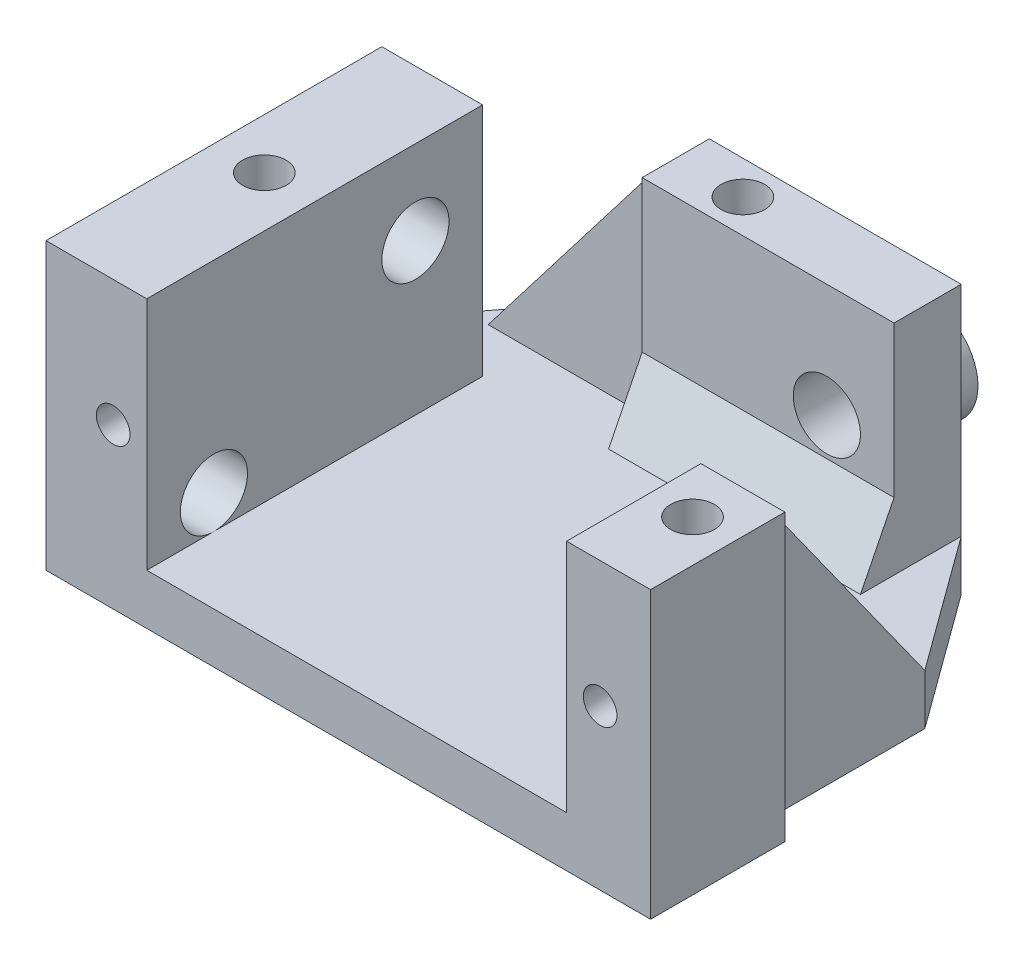
SolidWorks part; units mm, degrees
ref_plane "Front Plane" through (0, 0, 0) normal (0, 0, 1) x (1, 0, 0)
ref_plane "Top Plane" through (0, 0, 0) normal (0, 1, 0) x (1, 0, 0)
ref_plane "Right Plane" through (0, 0, 0) normal (1, 0, 0) x (0, 0, -1)
sketch "Sketch1" plane through (0, 0, 0) normal (0, 1, 0) x (1, 0, 0)
  line L1 (-25, 18) -> (25, 18)
  line L2 (-25, 18) -> (-25, -18)
  line L3 (-25, -18) -> (25, -18)
  line L4 (25, 18) -> (25, -18)
  point P4 (0, 18)
  point P6 (-25, 0)
  dimension "D1" = 50
  dimension "D2" = 36
extrude "Boss-Extrude1" add sketch "Sketch1" along normal blind 3
sketch "Sketch2" plane through (0, 3, 0) normal (0, 1, 0) x (1, 0, 0)
  line L0 (-25, -18) -> (25, -18) construction
  line L1 (25, -8) -> (20, -8)
  line L2 (25, -8) -> (25, 0)
  line L3 (25, 0) -> (20, 0)
  line L4 (20, -8) -> (20, 0)
  line L5 (-5, -8) -> (-11, -8)
  line L6 (-5, -8) -> (-5, 12)
  line L7 (-5, 12) -> (-11, 12)
  line L8 (-11, -8) -> (-11, 12)
  line L9 (25, -18) -> (25, 18) construction
  dimension "D1" = 25
  dimension "D2" = 8
  dimension "D3" = 10
  dimension "D4" = 5
  dimension "D5" = 0
  dimension "D6" = 20
  dimension "D7" = 6
extrude "Boss-Extrude2" add sketch "Sketch2" along normal blind 14
sketch "Sketch3" plane through (0, 3, 0) normal (0, 1, 0) x (1, 0, 0)
  line L0 (20, -8) -> (25, -8) construction
  line L1 (2.5, 14) -> (17.5, 14)
  line L2 (2.5, 14) -> (2.5, 18)
  line L3 (2.5, 18) -> (17.5, 18)
  line L4 (17.5, 14) -> (17.5, 18)
  line L5 (25, 0) -> (25, 18) construction
  dimension "D1" = 22
  dimension "D2" = 4
  dimension "D3" = 15
  dimension "D4" = 7.5
extrude "Boss-Extrude3" add sketch "Sketch3" along normal blind 13
sketch "Sketch4" plane through (0, 0, -18) normal (0, 0, -1) x (-1, 0, 0)
  line L0 (-25, 3) -> (-25, 0) construction
  line L2 (-25, 3) -> (-17.5, 3) construction
  circle A0 centre (-13.5, 9.25) radius 3
  point P4 (-13.5, 10.912)
  dimension "D1" = 11.5
  dimension "D2" = 6.25
  dimension "D3" = 6
extrude "Boss-Extrude4" add sketch "Sketch4" along normal blind 2 contours A0
sketch "Sketch5" plane through (0, 0, -20) normal (0, 0, -1) x (-1, 0, 0)
  circle A0 centre (-13.5, 9.25) radius 2
  dimension "D1" = 4
extrude "Cut-Extrude1" cut sketch "Sketch5" against normal blind 12
sketch "Sketch6" plane through (0, 3, 0) normal (0, 1, 0) x (1, 0, 0)
  line L0 (-11, 12) -> (-11, 18)
  line L1 (2.5, 18) -> (-25, 18) construction
  line L2 (-11, 18) -> (-25, 18)
  line L3 (-25, 18) -> (-25, -18)
  line L4 (-25, -18) -> (25, -18)
  line L5 (25, -18) -> (25, -8)
  line L6 (25, -8) -> (-11, -8)
  line L7 (-11, -8) -> (-11, 12)
extrude "Cut-Extrude2" cut sketch "Sketch6" against normal blind 11
sketch "Sketch7" plane through (0, 17, 0) normal (0, 1, 0) x (1, 0, 0)
  line L0 (25, 0) -> (20, 0) construction
  line L1 (23.3333, 0) -> (21.6667, 0)
  line L2 (23.3333, 0) -> (23.3333, 10)
  line L3 (23.3333, 10) -> (21.6667, 10)
  line L4 (21.6667, 0) -> (21.6667, 10)
  line L5 (25, 0) -> (25, 18) construction
  dimension "D1" = 1.6667
  dimension "D2" = 1.6667
  dimension "D3" = 10
extrude "Boss-Extrude5" add sketch "Sketch7" against normal up to surface (14 mm away) up to face at (8.1667, 3, -9)
sketch "Sketch8" plane through (23.3333, 0, 0) normal (1, 0, 0) x (0, 0, -1)
  line L0 (10, 3) -> (0, 17)
  line L1 (0, 17) -> (10, 17)
  line L2 (10, 17) -> (10, 3)
extrude "Cut-Extrude3" cut sketch "Sketch8" against normal up to next
sketch "Sketch9" plane through (0, 3, 0) normal (0, 1, 0) x (1, 0, 0)
  line L0 (25, 0) -> (23.3333, 0)
  line L1 (23.3333, 0) -> (23.3333, 10)
  line L2 (23.3333, 10) -> (17.5, 18)
  line L3 (17.5, 18) -> (25, 18)
  line L4 (25, 18) -> (25, 0)
extrude "Cut-Extrude4" cut sketch "Sketch9" against normal up to next contours L2 L3 L4 L0 L1
sketch "Sketch10" plane through (0, 3, 0) normal (0, 1, 0) x (1, 0, 0)
  line L0 (2.5, 18) -> (2.5, 14) construction
  line L1 (2.5, 14.8333) -> (-7.5, 14.8333)
  line L2 (2.5, 14.8333) -> (2.5, 16.5)
  line L3 (2.5, 16.5) -> (-7.5, 16.5)
  line L4 (-7.5, 14.8333) -> (-7.5, 16.5)
  line L5 (21.6667, 10) -> (23.3333, 10) construction
  line L6 (2.5, 18) -> (-11, 18) construction
  dimension "D1" = 10
  dimension "D2" = 1.5
extrude "Boss-Extrude7" add sketch "Sketch10" along normal up to surface (13 mm away) up to face at (10, 16, -16)
sketch "Sketch11" plane through (0, 0, -16.5) normal (0, 0, -1) x (-1, 0, 0)
  line L0 (7.5, 3) -> (-2.5, 16)
  line L1 (-2.5, 16) -> (7.5, 16)
  line L2 (7.5, 16) -> (7.5, 3)
extrude "Cut-Extrude5" cut sketch "Sketch11" against normal blind 2
sketch "Sketch12" plane through (-11, 0, 0) normal (-1, 0, 0) x (0, 0, 1)
  line L0 (-12, 17) -> (8, 17) construction
  line L1 (8, 17) -> (8, 0) construction
  line L2 (-12, 17) -> (-12, 3) construction
  circle A0 centre (4, 5) radius 2
  circle A1 centre (-8, 12) radius 2
  point P4 (0, 0)
  dimension "D1" = 4
  dimension "D2" = 12
  dimension "D3" = 4
  dimension "D4" = 4
  dimension "D5" = 5
extrude "Cut-Extrude6" cut sketch "Sketch12" against normal blind 6
chamfer "Chamfer1" distance 2 distance2 4 1 edges at (10, 3, -14)
sketch "Sketch13" plane through (0, 3, 0) normal (0, 1, 0) x (1, 0, 0)
  line L0 (-7.5, 16.5) -> (-11, 12)
  line L1 (-11, 12) -> (-11, 18)
  line L2 (-11, 18) -> (2.5, 18)
  line L3 (2.5, 18) -> (2.5, 16.5)
  line L4 (-7.5, 16.5) -> (2.5, 16.5)
extrude "Cut-Extrude7" cut sketch "Sketch13" against normal blind 5
sketch "Sketch14" plane through (0, 17, 0) normal (0, 1, 0) x (1, 0, 0)
  line L0 (-5, 12) -> (-11, 12) construction
  line L2 (21.6667, 0) -> (23.3333, 0) construction
  line L3 (25, 0) -> (23.3333, 0) construction
  line L4 (17.5, 14) -> (17.5, 18) construction
  line L5 (2.5, 18) -> (2.5, 16.5) construction
  line L6 (-11, 12) -> (-11, -8) construction
  circle A0 centre (6.5, 16) radius 1.3
  circle A1 centre (-8, 2) radius 1.3
  circle A2 centre (22.5, -3) radius 1.3
  point P6 (0, 0)
  point P9 (-8, 12)
  point P10 (0, 0)
  point P14 (0, 0)
  point P17 (22.5, 0)
  point P21 (0, 0)
  point P24 (17.5, 16)
  point P27 (0, 0)
  point P30 (-11, 2)
  dimension "D1" = 2.6
  dimension "D2" = 3
  dimension "D3" = 4
extrude "Cut-Extrude8" cut sketch "Sketch14" against normal blind 6
sketch "Sketch15" plane through (0, 0, 8) normal (0, 0, 1) x (1, 0, 0)
  line L0 (-7.5, 3) -> (2.5, 3) construction
  line L1 (-5, 17) -> (-5, 3) construction
  line L2 (20, 17) -> (20, 3) construction
  circle A0 centre (-7, 9.5) radius 1
  circle A1 centre (22, 9.5) radius 1
  point P4 (0, 0)
  point P7 (-6.7208, 9.5)
  dimension "D1" = 2
  dimension "D4" = 2
  dimension "D5" = 2
  dimension "D2" = 6.5
  dimension "D3" = 29
extrude "Cut-Extrude9" cut sketch "Sketch15" against normal blind 6
equation "\"D2@Sketch10\"=1.5"
